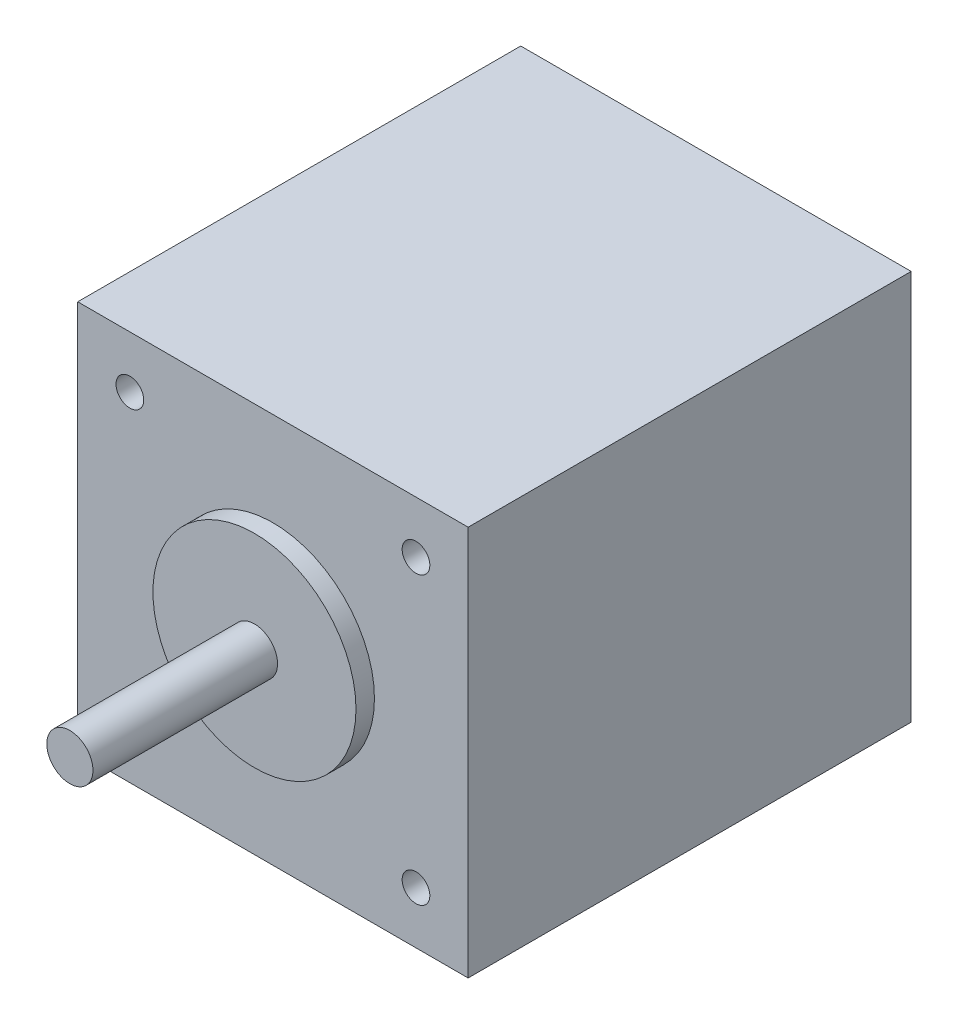
SolidWorks part; units mm, degrees
ref_plane "Ebene vorne" through (0, 0, 0) normal (0, 0, 1) x (1, 0, 0)
ref_plane "Ebene oben" through (0, 0, 0) normal (0, 1, 0) x (1, 0, 0)
ref_plane "Ebene rechts" through (0, 0, 0) normal (1, 0, 0) x (0, 0, -1)
sketch "Skizze1" plane through (0, 0, 0) normal (0, 0, 1) x (1, 0, 0)
  line L1 (-21.15, -21.15) -> (21.15, -21.15)
  line L2 (-21.15, -21.15) -> (-21.15, 21.15)
  line L3 (-21.15, 21.15) -> (21.15, 21.15)
  line L4 (21.15, -21.15) -> (21.15, 21.15)
  line L5 (-21.15, -21.15) -> (21.15, 21.15) construction
  line L6 (-21.15, 21.15) -> (21.15, -21.15) construction
  point P0 (0, 0)
  dimension "D1" = 42.3
extrude "Aufsatz-Linear austragen1" add sketch "Skizze1" along normal blind 48
sketch "Skizze2" plane through (0, 0, 48) normal (0, 0, 1) x (1, 0, 0)
  circle A0 centre (0, 0) radius 11
  dimension "D1" = 22
extrude "Aufsatz-Linear austragen2" add sketch "Skizze2" along normal blind 2
sketch "Skizze3" plane through (0, 0, 50) normal (0, 0, 1) x (1, 0, 0)
  circle A0 centre (0, 0) radius 2.5
  dimension "D1" = 5
extrude "Aufsatz-Linear austragen3" add sketch "Skizze3" along normal blind 20
sketch "Skizze4" plane through (0, 0, 48) normal (0, 0, 1) x (1, 0, 0)
  line L1 (-15.5, -15.5) -> (15.5, -15.5) construction
  line L2 (-15.5, -15.5) -> (-15.5, 15.5) construction
  line L3 (-15.5, 15.5) -> (15.5, 15.5) construction
  line L4 (15.5, -15.5) -> (15.5, 15.5) construction
  line L5 (-15.5, -15.5) -> (15.5, 15.5) construction
  line L6 (-15.5, 15.5) -> (15.5, -15.5) construction
  circle A0 centre (-15.5, 15.5) radius 1.5
  circle A1 centre (15.5, 15.5) radius 1.5
  circle A2 centre (15.5, -15.5) radius 1.5
  circle A3 centre (-15.5, -15.5) radius 1.5
  point P0 (0, 0)
  dimension "D3" = 3
  dimension "D1" = 31
  dimension "D2" = 31
extrude "Schnitt-Linear austragen1" cut sketch "Skizze4" against normal blind 4
